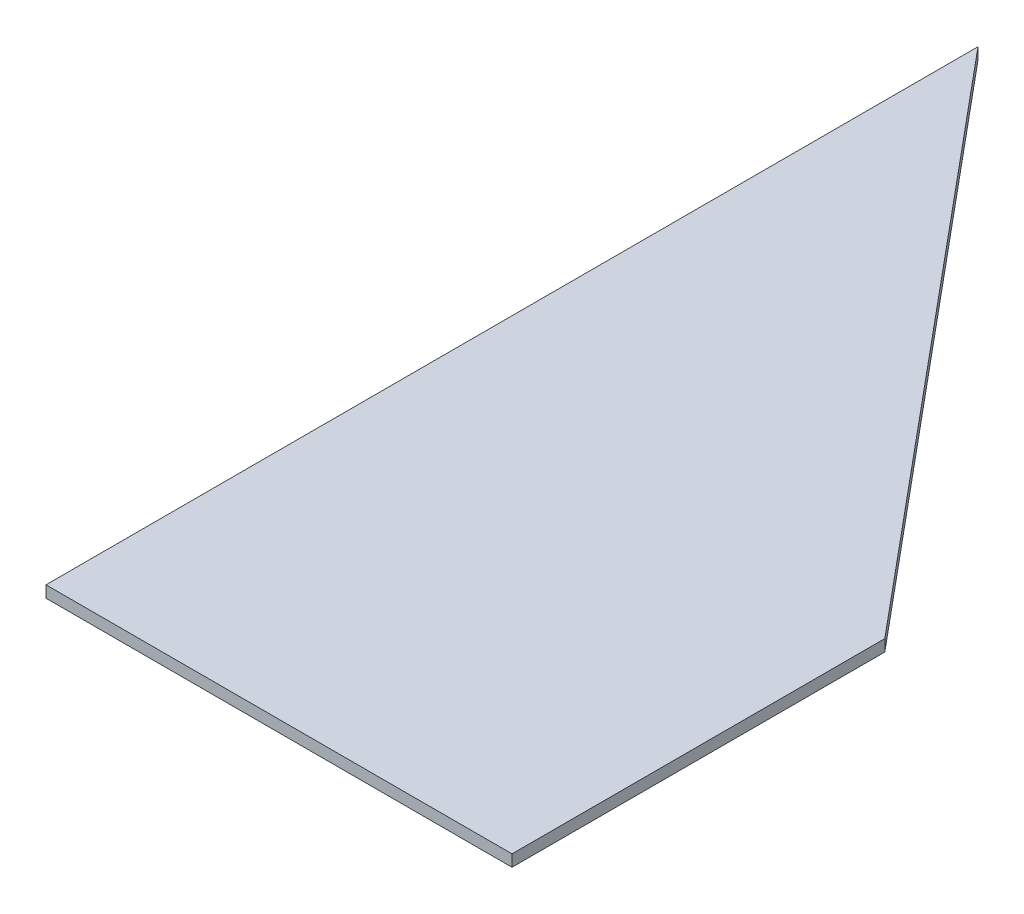
SolidWorks part; units mm, degrees
other "cfbottom"
other "cftop"
other "finbody"
ref_plane "Front Plane" through (0, 0, 0) normal (0, 0, 1) x (1, 0, 0)
ref_plane "Top Plane" through (0, 0, 0) normal (0, 1, 0) x (1, 0, 0)
ref_plane "Right Plane" through (0, 0, 0) normal (1, 0, 0) x (0, 0, -1)
sketch "Sketch1" plane through (0, 0, 0) normal (0, 1, 0) x (1, 0, 0)
  line L0 (0, 0) -> (0, 254)
  line L1 (0, 254) -> (127, 101.6)
  line L2 (127, 101.6) -> (127, 0)
  line L3 (127, 0) -> (0, 0)
  dimension "D1" = 254
  dimension "D2" = 127
  dimension "D3" = 101.6
extrude "FinBody" add sketch "Sketch1" along normal blind 3.175
ref_plane "Midplane" through (0, 1.5875, 0) normal (0, 1, 0) x (1, 0, 0)
